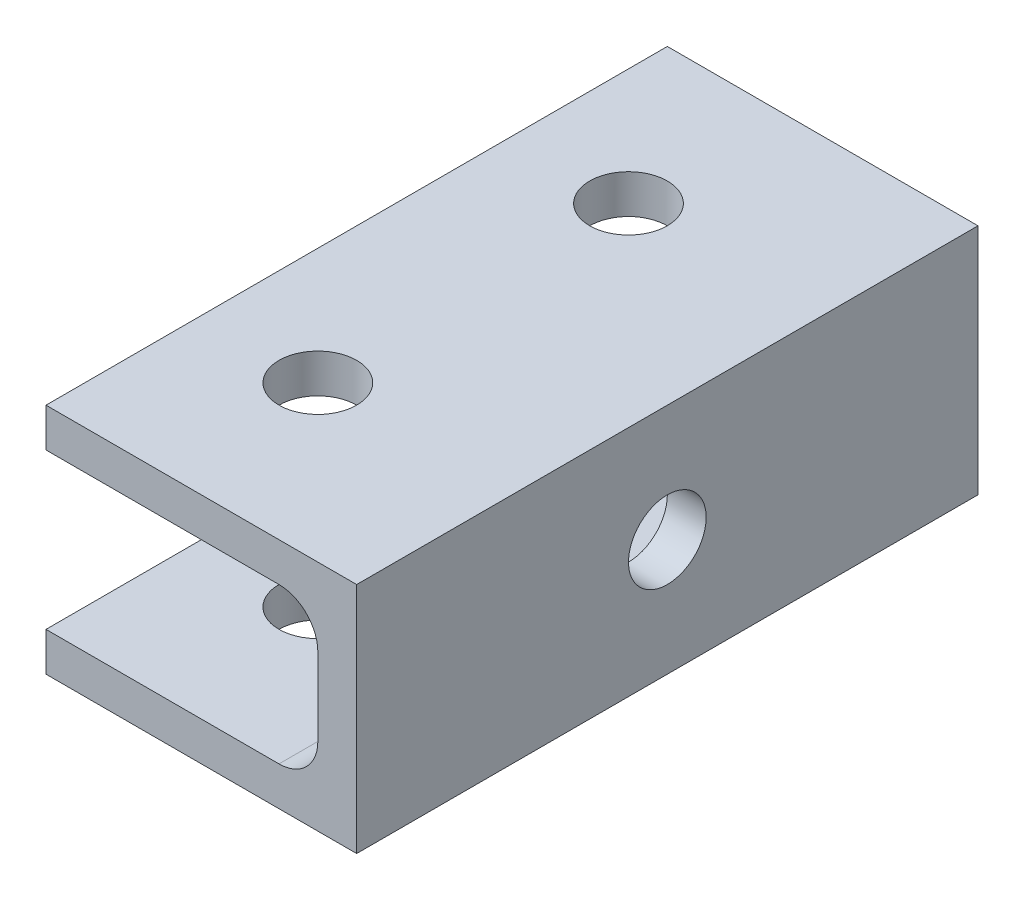
SolidWorks part; units mm, degrees
ref_plane "Front Plane" through (0, 0, 0) normal (0, 0, 1) x (1, 0, 0)
ref_plane "Top Plane" through (0, 0, 0) normal (0, 1, 0) x (1, 0, 0)
ref_plane "Right Plane" through (0, 0, 0) normal (1, 0, 0) x (0, 0, -1)
sketch "Sketch1" plane through (0, 0, 0) normal (0, 0, 1) x (1, 0, 0)
  line L0 (0, 0) -> (35, 0)
  line L1 (35, 0) -> (35, -20)
  line L2 (35, -20) -> (0, -20)
  line L3 (0, -20) -> (0, -25)
  line L4 (0, -25) -> (40, -25)
  line L5 (40, -25) -> (40, 5)
  line L6 (40, 5) -> (0, 5)
  line L7 (0, 5) -> (0, 0)
  dimension "D1" = 5
  dimension "D2" = 5
  dimension "D3" = 5
  dimension "D4" = 35
  dimension "D5" = 20
extrude "Boss-Extrude1" add sketch "Sketch1" along normal blind 80
fillet "Fillet1" radius 5 2 edges at (35, -20, 40) (35, 0, 40)
sketch "Sketch2" plane through (0, 5, 0) normal (0, 1, 0) x (1, 0, 0)
  line L0 (0, -40) -> (40, -40) construction
  line L1 (0, -80) -> (0, 0) construction
  line L2 (40, -80) -> (40, 0) construction
  circle A0 centre (15, -60) radius 5
  circle A2 centre (15, -20) radius 5
  dimension "D1" = 20
  dimension "D2" = 10
  dimension "D3" = 15
extrude "Cut-Extrude1" cut sketch "Sketch2" against normal blind 75 contours A0 | A2
sketch "Sketch3" plane through (40, 0, 0) normal (1, 0, 0) x (0, 0, -1)
  line L0 (0, -25) -> (0, 5) construction
  line L2 (-80, -25) -> (0, -25) construction
  circle A0 centre (-40, -10) radius 5
  point P4 (0, 0)
  point P6 (-42.8973, -25)
  dimension "D1" = 40
  dimension "D2" = 15
extrude "Cut-Extrude2" cut sketch "Sketch3" against normal blind 10
